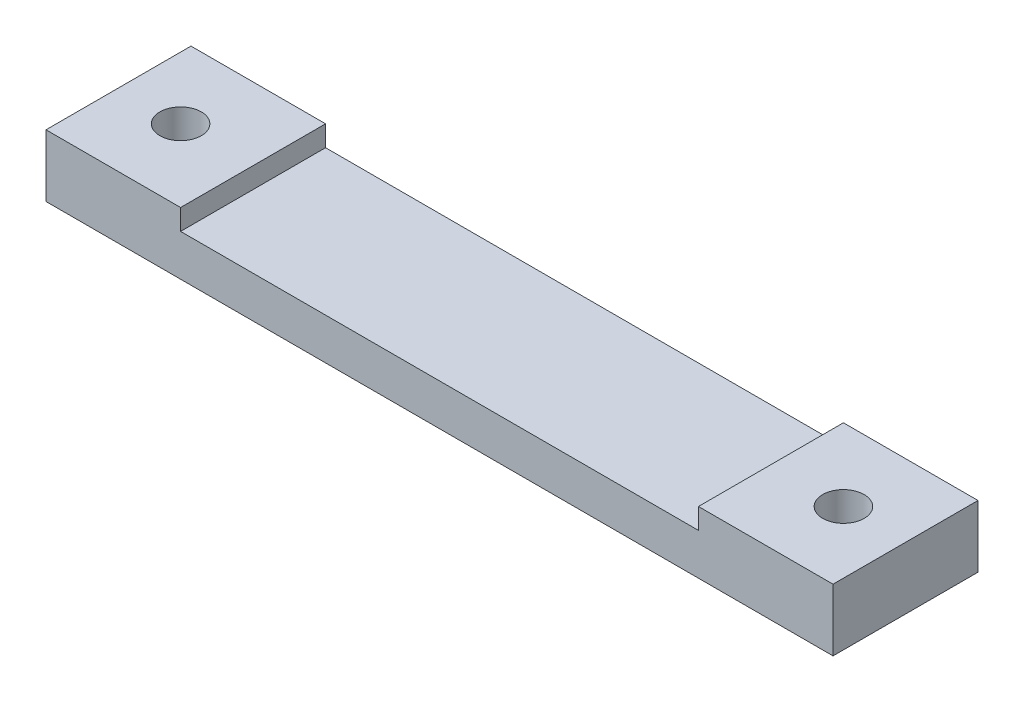
SolidWorks part; units mm, degrees
ref_plane "Front Plane" through (0, 0, 0) normal (0, 0, 1) x (1, 0, 0)
ref_plane "Top Plane" through (0, 0, 0) normal (0, 1, 0) x (1, 0, 0)
ref_plane "Right Plane" through (0, 0, 0) normal (1, 0, 0) x (0, 0, -1)
sketch "Sketch1" plane through (0, 0, 0) normal (0, 1, 0) x (1, 0, 0)
  line L0 (0, 27.4631) -> (0, -27.4196) construction
  line L1 (0, -27.4196) -> (0, 0) construction
  line L2 (0, 0) -> (-38.3414, 0) construction
  line L3 (-38.3414, 0) -> (41.1483, 0) construction
  line L5 (-19, 3.5) -> (19, 3.5)
  line L6 (-19, 3.5) -> (-19, -3.5)
  line L7 (-19, -3.5) -> (19, -3.5)
  line L8 (19, 3.5) -> (19, -3.5)
  dimension "D1" = 38
  dimension "D2" = 7
  dimension "D3" = 19
  dimension "D4" = 3.5
extrude "Boss-Extrude1" add sketch "Sketch1" along normal blind 2
sketch "Sketch2" plane through (0, 2, 0) normal (0, 1, 0) x (1, 0, 0)
  line L0 (-19, -3.5) -> (19, -3.5) construction
  line L1 (-19, 3.5) -> (-12.5013, 3.5)
  line L2 (-19, 3.5) -> (-19, -3.5)
  line L3 (-19, -3.5) -> (-12.5013, -3.5)
  line L4 (-12.5013, 3.5) -> (-12.5013, -3.5)
  line L6 (19, 3.5) -> (12.5022, 3.5)
  line L7 (19, 3.5) -> (19, -3.5)
  line L8 (19, -3.5) -> (12.5022, -3.5)
  line L9 (12.5022, 3.5) -> (12.5022, -3.5)
extrude "Boss-Extrude2" add sketch "Sketch2" along normal blind 1
sketch "Sketch3" plane through (0, 3, 0) normal (0, 1, 0) x (1, 0, 0)
  line L0 (-12.5013, -3.5) -> (-12.5013, 3.5) construction
  line L1 (-19, -3.5) -> (-12.5013, -3.5) construction
  line L2 (12.5022, 3.5) -> (12.5022, -3.5) construction
  line L3 (12.5022, -3.5) -> (19, -3.5) construction
  circle A0 centre (-16.0013, 0) radius 1
  circle A1 centre (16.0022, 0) radius 1
  dimension "D1" = 3.5
  dimension "D3" = 3.5
  dimension "D2" = 3.5
  dimension "D4" = 3.5
extrude "Cut-Extrude1" cut sketch "Sketch3" against normal blind 3
